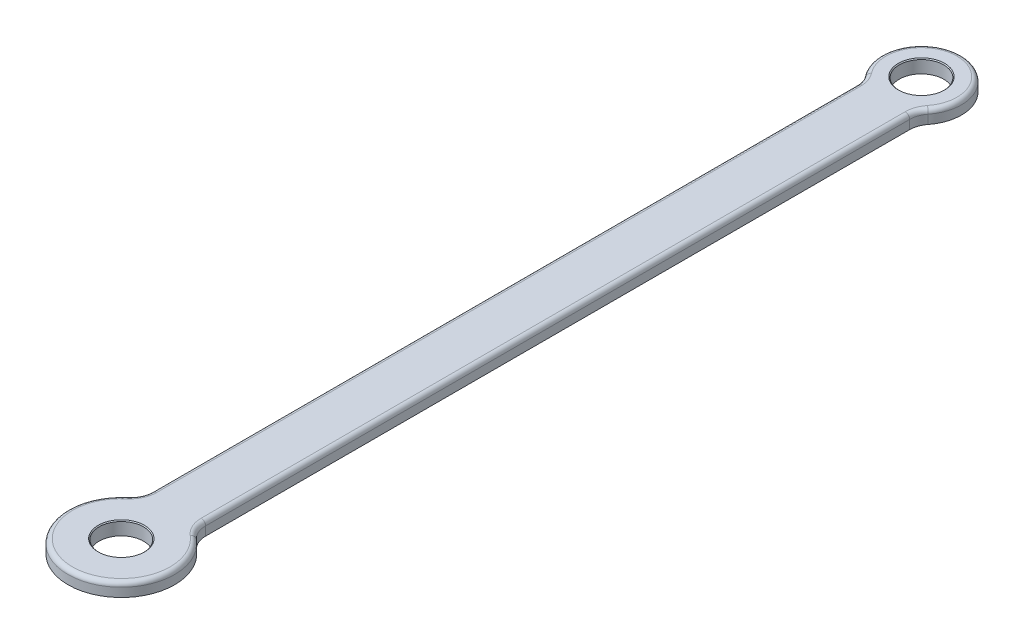
SolidWorks part; units mm, degrees
ref_plane "前视基准面" through (0, 0, 0) normal (0, 0, 1) x (1, 0, 0)
ref_plane "上视基准面" through (0, 0, 0) normal (0, 1, 0) x (1, 0, 0)
ref_plane "右视基准面" through (0, 0, 0) normal (1, 0, 0) x (0, 0, -1)
other "Configuration Table"
sketch "草图1" plane through (0, 0, 0) normal (0, 1, 0) x (1, 0, 0)
  line L0 (-4, -4.4721) -> (-4, -113.0718)
  line L1 (4, -4.4721) -> (4, -113.0718)
  line L2 (0, 0) -> (0, 32.1018) construction
  arc A0 (4, -4.4721) -> (-4, -4.4721) centre (0, 0) ccw
  arc A1 (-4, -113.0718) -> (4, -113.0718) centre (0, -120) ccw
  circle A2 centre (0, 0) radius 3.3333
  circle A3 centre (0, -120) radius 3.3333
  dimension "D1" = 12
  dimension "D2" = 16
  dimension "D3" = 120
  dimension "D5" = 6.6667
  dimension "D6" = 6.6667
  dimension "D4" = 8
extrude "凸台-拉伸1" add sketch "草图1" along normal blind 2
scale "缩放比例1" scale about centroid uniform scaling yes scale factor 1.5
chamfer "倒角1" distance 0.2 angle 45 2 edges at (0, 2.5, 153.0136) (0, 2.5, -26.9864)
fillet "圆角1" radius 5 4 edges at (6, 1, 137.6213) (-6, 1, 137.6213) (-6, 1, -25.2782) (6, 1, -25.2782)
fillet "圆角2" radius 1 8 edges at (-6.2754, 2.5, -24.9628) (0, 2.5, -40.9864) (6.2754, 2.5, -24.9628) (6, 2.5, 55.863) (6.4626, 2.5, 137.1525) (0, 2.5, 160.0136) (-6.4626, 2.5, 137.1525) (-6, 2.5, 55.863)
